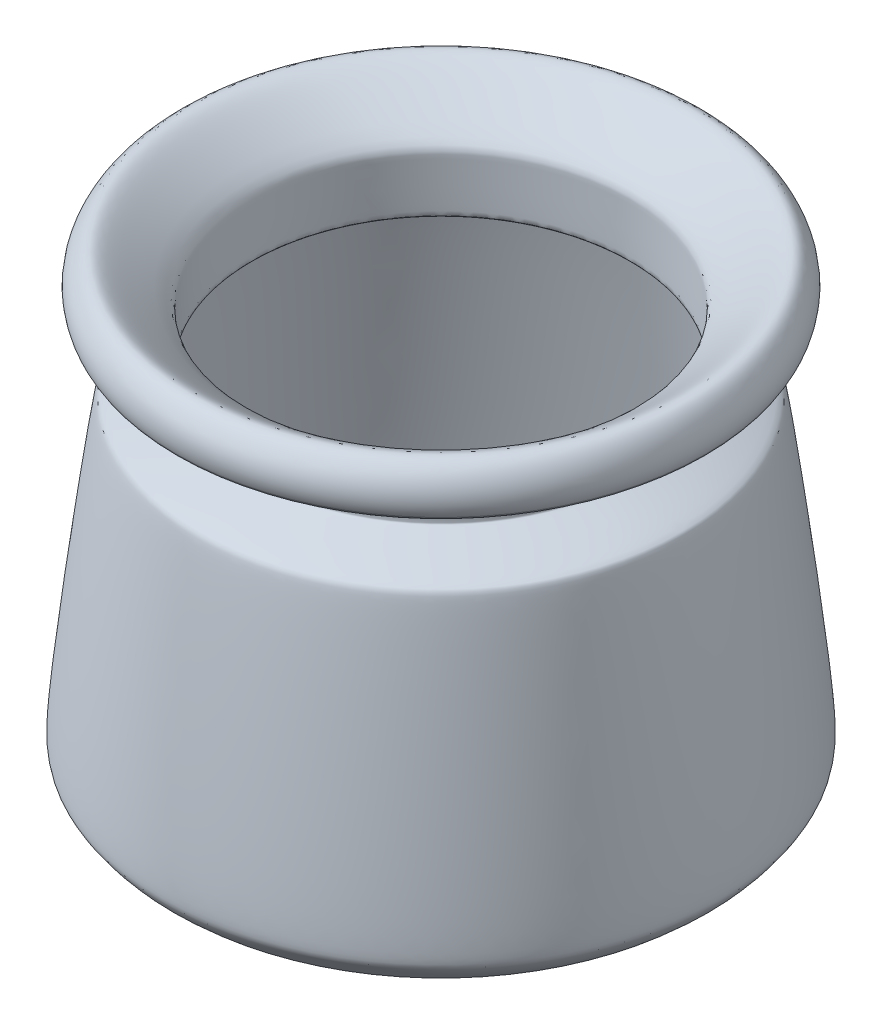
SolidWorks part; units mm, degrees
material "AISI 304"
ref_plane "Front Plane" through (0, 0, 0) normal (0, 0, 1) x (1, 0, 0)
ref_plane "Top Plane" through (0, 0, 0) normal (0, 1, 0) x (1, 0, 0)
ref_plane "Right Plane" through (0, 0, 0) normal (1, 0, 0) x (0, 0, -1)
sketch "Sketch1" plane through (0, 0, 0) normal (0, 0, 1) x (1, 0, 0)
  line L0 (0, 278.8627) -> (0, -254.1465) construction
  line L1 (246.38, 137.301) -> (296.3973, 137.301)
  line L2 (296.3973, 137.301) -> (296.3973, 217.6046)
  line L3 (296.3973, 217.6046) -> (0, 217.6046)
  line L4 (0, 217.6046) -> (0, -254.1465)
  spline S0 degree 3 poles (0, -254.1465) (109.3081, -254.0622) (126.7627, -254.1888) (149.9682, -254.1675) (231.4419, -247.6332) (247.8116, -240.8422) (259.869, -226.0921) (267.178, -210.9116) (233.0202, 59.004) (226.7626, 67.3371) (180.3823, 83.5415) (179.2299, 84.4601) (179.7826, 128.4716) (179.7643, 137.9343) (187.7477, 145.8014) (225.1192, 175.239) (232.5418, 178.5635) (245.2417, 175.7707) (256.9335, 152.4707) (246.38, 137.301) knots 0 0 0 0 0.077984 0.094799 0.159999 0.179903 0.273939 0.302113 0.43347 0.46241 0.562567 0.584872 0.663153 0.680356 0.739704 0.755891 0.826046 0.851333 1 1 1 1
  dimension "D1" = 139.7
  dimension "D2" = 262.636
  dimension "D3" = 25.4
  dimension "D4" = 317.5
  dimension "D5" = 229.108
  dimension "D6" = 179.832
  dimension "D7" = 179.832
  dimension "D8" = 236.22
  dimension "D9" = 246.38
  dimension "D10" = 431.8
revolve "Revolve1" add sketch "Sketch1" angle 360 about L4
shell "Shell1" thickness 2
sketch "Sketch2" plane through (0, 0, 0) normal (0, 0, 1) x (1, 0, 0)
  line L0 (0, 0) -> (0, 208.5793) construction
  line L1 (-249.9122, 139.301) -> (-248.6779, 137.301)
  line L4 (249.9122, 139.301) -> (-249.9122, 139.301) construction
  line L5 (-296.3973, 137.301) -> (296.3973, 137.301) construction
  line L6 (-248.6779, 137.301) -> (-248.5439, 136.6587)
  line L7 (-248.5439, 136.6587) -> (-302.071, 132.99)
  line L8 (-302.071, 132.99) -> (-302.071, 230.0994)
  line L9 (-302.071, 230.0994) -> (-257.6984, 220.3371)
  line L10 (-257.6984, 220.3371) -> (-256.1913, 145.1097)
  line L11 (-256.1913, 145.1097) -> (-249.9122, 139.301)
revolve "Cut-Revolve1" cut sketch "Sketch2" angle 360 about L0
fillet "Fillet1" radius 0.762 2 edges at (0, 137.301, -248.6779) (0, 137.301, 246.38)
